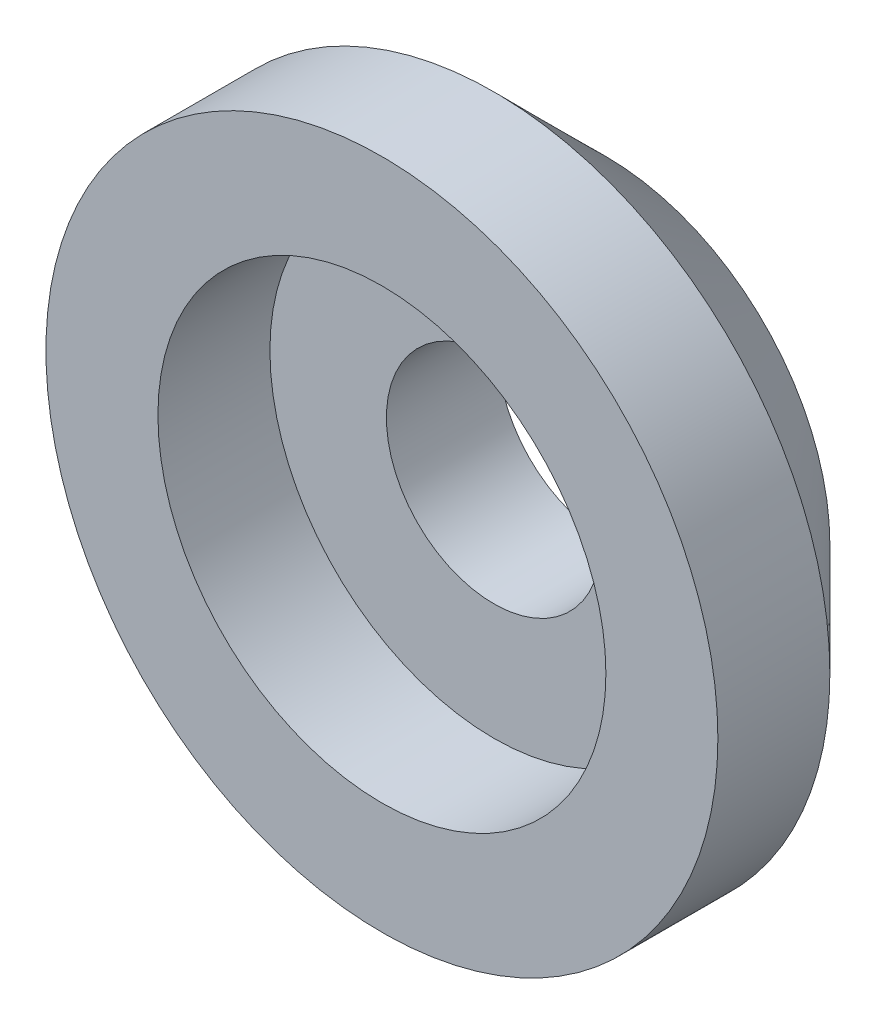
SolidWorks part; units mm, degrees
ref_plane "前视基准面" through (0, 0, 0) normal (0, 0, 1) x (1, 0, 0)
ref_plane "上视基准面" through (0, 0, 0) normal (0, 1, 0) x (1, 0, 0)
ref_plane "右视基准面" through (0, 0, 0) normal (1, 0, 0) x (0, 0, -1)
other "Configuration Table"
sketch "Sketch1" plane through (0, 0, 0) normal (0, 0, 1) x (1, 0, 0)
  circle A0 centre (0, 0) radius 7.5
  dimension "D1" = 15
extrude "Boss-Extrude1" add sketch "Sketch1" along normal blind 5
sketch "Sketch2" plane through (0, 0, 5) normal (0, 0, 1) x (1, 0, 0)
  circle A0 centre (0, 0) radius 5
  dimension "D1" = 10
extrude "Cut-Extrude1" cut sketch "Sketch2" against normal blind 2.5
chamfer "Chamfer1" distance 2.5 angle 45 1 edges at (7.5, 0, 0)
sketch "Sketch3" plane through (0, 0, 2.5) normal (0, 0, 1) x (1, 0, 0)
  circle A2 centre (0, 0) radius 2.4
  dimension "D1" = 4.8
extrude "Cut-Extrude2" cut sketch "Sketch3" against normal blind 2.5
